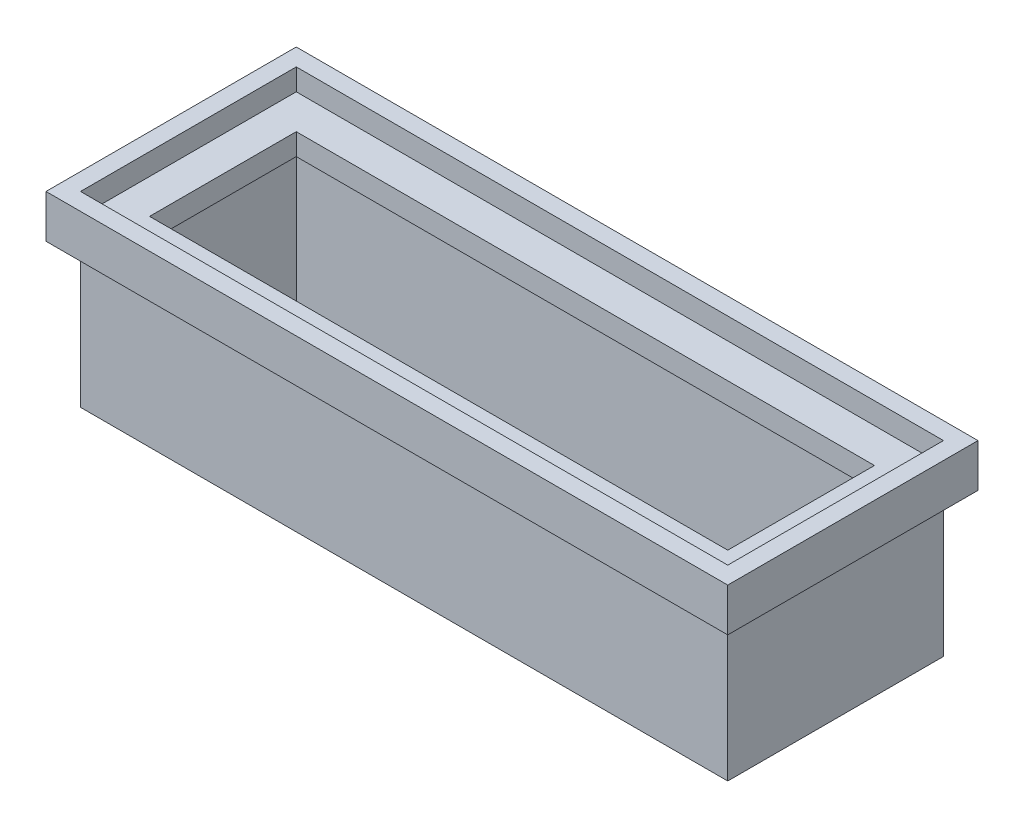
SolidWorks part; units mm, degrees
ref_plane "Front Plane" through (0, 0, 0) normal (0, 0, 1) x (1, 0, 0)
ref_plane "Top Plane" through (0, 0, 0) normal (0, 1, 0) x (1, 0, 0)
ref_plane "Right Plane" through (0, 0, 0) normal (1, 0, 0) x (0, 0, -1)
sketch "Sketch2" plane through (0, 0, 0) normal (0, 1, 0) x (1, 0, 0)
  line L1 (-26.8763, 8.9474) -> (15.7237, 8.9474)
  line L2 (-26.8763, 8.9474) -> (-26.8763, -3.6526)
  line L3 (-26.8763, -3.6526) -> (15.7237, -3.6526)
  line L4 (15.7237, 8.9474) -> (15.7237, -3.6526)
  dimension "D1" = 12.6
  dimension "D2" = 42.6
extrude "Extrude-Thin1" add sketch "Sketch2" along normal blind 10 thin contours L1 L4 L3 L2 thin type one direction wall 1.2
sketch "Sketch5" plane through (0, 10, 0) normal (0, 1, 0) x (1, 0, 0)
  line L0 (-28.0763, 10.1474) -> (16.9237, 10.1474) construction
  line L1 (-28.0763, 10.1474) -> (-25.6763, 10.1474)
  line L2 (-25.6763, 10.1474) -> (-25.6763, 7.7474) construction
  line L3 (16.9237, -4.8526) -> (14.5237, -4.8526) construction
  line L4 (-28.0763, -4.8526) -> (16.9237, -4.8526) construction
  line L5 (14.5237, -4.8526) -> (14.5237, -2.4526) construction
  line L7 (-25.6763, 7.7474) -> (14.5237, 7.7474)
  line L8 (-25.6763, 7.7474) -> (-25.6763, -2.4526)
  line L9 (-25.6763, -2.4526) -> (14.5237, -2.4526)
  line L10 (14.5237, 7.7474) -> (14.5237, -2.4526)
  dimension "D1" = 2.4
extrude "Extrude-Thin3" add sketch "Sketch5" along normal blind 3 thin contours L7 L10 L9 L8
sketch "Sketch6" plane through (0, 13, 0) normal (0, 1, 0) x (1, 0, 0)
  line L0 (-29.2763, 11.3474) -> (-28.0763, 11.3474) construction
  line L1 (-29.2763, 11.3474) -> (18.1237, 11.3474) construction
  line L2 (-28.0763, 11.3474) -> (-28.0763, 10.1474) construction
  line L3 (18.1237, -6.0526) -> (16.9237, -6.0526) construction
  line L4 (-29.2763, -6.0526) -> (18.1237, -6.0526) construction
  line L5 (16.9237, -6.0526) -> (16.9237, -4.8526) construction
  line L7 (-28.0763, 10.1474) -> (16.9237, 10.1474)
  line L8 (-28.0763, 10.1474) -> (-28.0763, -4.8526)
  line L9 (-28.0763, -4.8526) -> (16.9237, -4.8526)
  line L10 (16.9237, 10.1474) -> (16.9237, -4.8526)
extrude "Cut-Extrude2" cut sketch "Sketch6" against normal blind 1.5 contours L8 L9 L10 L7
